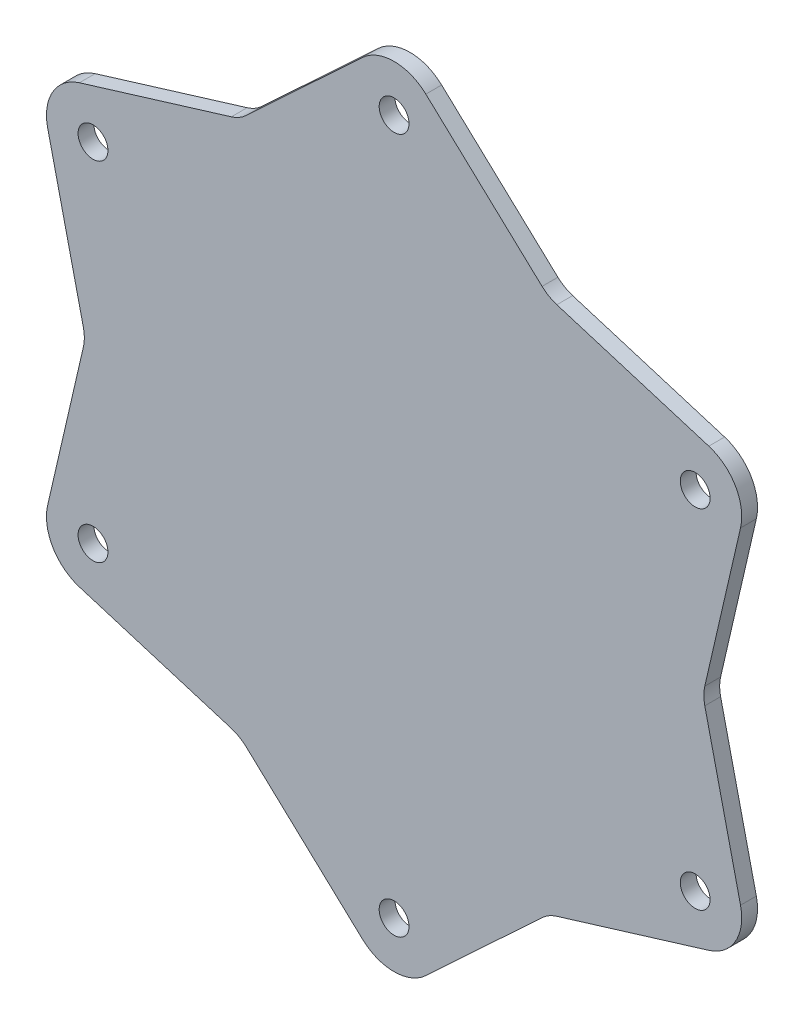
SolidWorks part; units mm, degrees
material "6061 Alloy"
ref_plane "Front Plane" through (0, 0, 0) normal (0, 0, 1) x (1, 0, 0)
ref_plane "Top Plane" through (0, 0, 0) normal (0, 1, 0) x (1, 0, 0)
ref_plane "Right Plane" through (0, 0, 0) normal (1, 0, 0) x (0, 0, -1)
sketch "Sketch1" plane through (0, 0, 0) normal (0, 0, 1) x (1, 0, 0)
  line L0 (0, 0) -> (0, 69.85) construction
  line L1 (0, 0) -> (34.925, 60.4919) construction
  line L2 (6.3757, 76.6891) -> (29.729, 54.9182)
  line L3 (-6.3757, 76.6891) -> (-29.729, 54.9182)
  line L4 (63.2269, 43.866) -> (32.6961, 53.2052)
  line L5 (69.6025, 32.823) -> (62.425, 1.713)
  line L6 (69.6025, -32.823) -> (62.425, -1.713)
  line L7 (63.2269, -43.866) -> (32.6961, -53.2052)
  line L8 (6.3757, -76.6891) -> (29.729, -54.9182)
  line L9 (-6.3757, -76.6891) -> (-29.729, -54.9182)
  line L10 (-63.2269, -43.866) -> (-32.6961, -53.2052)
  line L11 (-69.6025, -32.823) -> (-62.425, -1.713)
  line L12 (-69.6025, 32.823) -> (-62.425, 1.713)
  line L13 (-63.2269, 43.866) -> (-32.6961, 53.2052)
  circle A0 centre (0, 0) radius 69.85 construction
  circle A1 centre (0, 69.85) radius 3
  arc A2 (6.3757, 76.6891) -> (-6.3757, 76.6891) centre (0, 69.85) ccw
  arc A5 (29.729, 54.9182) -> (32.6961, 53.2052) centre (34.925, 60.4919) ccw
  arc A6 (69.6025, 32.823) -> (63.2269, 43.866) centre (60.4919, 34.925) ccw
  circle A7 centre (60.4919, 34.925) radius 3
  arc A8 (62.425, 1.713) -> (62.425, -1.713) centre (69.85, 0) ccw
  arc A9 (63.2269, -43.866) -> (69.6025, -32.823) centre (60.4919, -34.925) ccw
  circle A10 centre (60.4919, -34.925) radius 3
  arc A11 (32.6961, -53.2052) -> (29.729, -54.9182) centre (34.925, -60.4919) ccw
  arc A12 (-6.3757, -76.6891) -> (6.3757, -76.6891) centre (0, -69.85) ccw
  circle A13 centre (0, -69.85) radius 3
  arc A14 (-29.729, -54.9182) -> (-32.6961, -53.2052) centre (-34.925, -60.4919) ccw
  arc A15 (-69.6025, -32.823) -> (-63.2269, -43.866) centre (-60.4919, -34.925) ccw
  circle A16 centre (-60.4919, -34.925) radius 3
  arc A17 (-62.425, -1.713) -> (-62.425, 1.713) centre (-69.85, 0) ccw
  arc A18 (-63.2269, 43.866) -> (-69.6025, 32.823) centre (-60.4919, 34.925) ccw
  circle A19 centre (-60.4919, 34.925) radius 3
  arc A20 (-32.6961, 53.2052) -> (-29.729, 54.9182) centre (-34.925, 60.4919) ccw
  point P5 (32.6961, 53.2052)
  point P55 (0, 0)
  dimension "D1" = 139.7
  dimension "D2" = 6
  dimension "D3" = 6.35
  dimension "D4" = 30
  dimension "D6" = 7.62
  dimension "D5" = 6
extrude "Boss-Extrude2" add sketch "Sketch1" along normal blind 3.175
